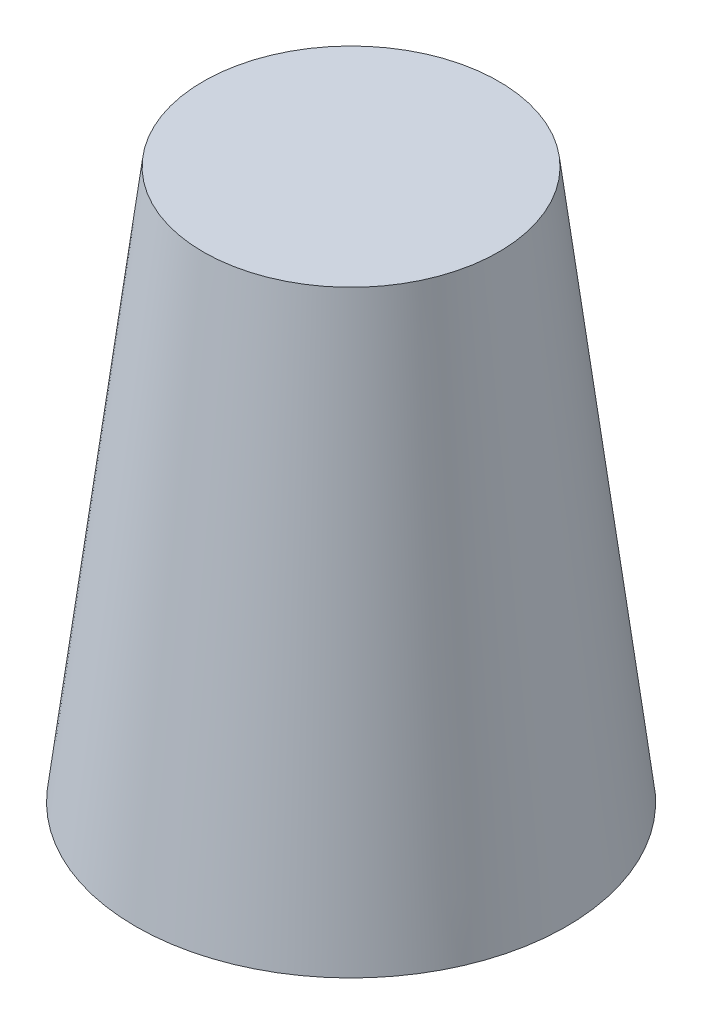
SolidWorks part; units mm, degrees
ref_plane "Front Plane" through (0, 0, 0) normal (0, 0, 1) x (1, 0, 0)
ref_plane "Top Plane" through (0, 0, 0) normal (0, 1, 0) x (1, 0, 0)
ref_plane "Right Plane" through (0, 0, 0) normal (1, 0, 0) x (0, 0, -1)
sketch "Sketch2" plane through (0, 0, 0) normal (0, 1, 0) x (1, 0, 0)
  circle A0 centre (0, 0) radius 90
  dimension "D1" = 180
extrude "Boss-Extrude1" add sketch "Sketch2" along normal blind 230 draft 7
sketch "Sketch3" plane through (0, 0, 0) normal (0, -1, 0) x (1, 0, 0)
  circle A0 centre (0, 0) radius 85
  dimension "D1" = 170
extrude "Cut-Extrude1" cut sketch "Sketch3" against normal blind 220 draft 7
